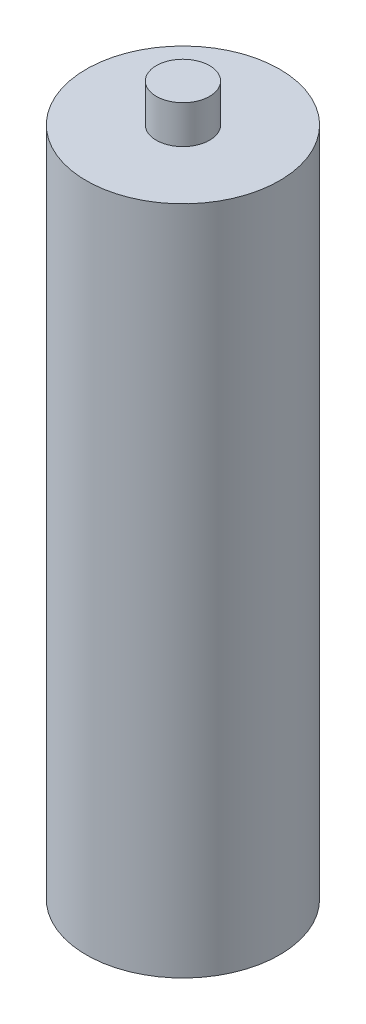
SolidWorks part; units mm, degrees
ref_plane "前视基准面" through (0, 0, 0) normal (0, 0, 1) x (1, 0, 0)
ref_plane "上视基准面" through (0, 0, 0) normal (0, 1, 0) x (1, 0, 0)
ref_plane "右视基准面" through (0, 0, 0) normal (1, 0, 0) x (0, 0, -1)
other "Configuration Table"
sketch "草图1" plane through (0, 0, 0) normal (0, 1, 0) x (1, 0, 0)
  circle A0 centre (0, 0) radius 50.8
extrude "凸台-拉伸1" add sketch "草图1" along normal blind 352.425
sketch "草图2" plane through (0, 352.425, 0) normal (0, 1, 0) x (1, 0, 0)
  circle A0 centre (0, 0) radius 14
extrude "凸台-拉伸2" add sketch "草图2" along normal blind 20
